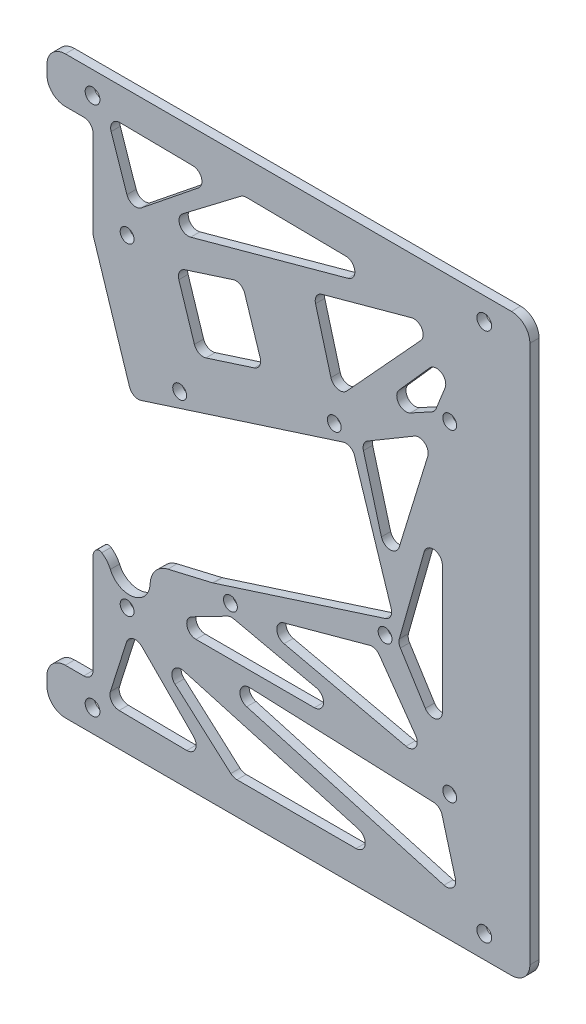
SolidWorks part; units mm, degrees
material "Thornel Mat VMA"
ref_plane "前视基准面" through (0, 0, 0) normal (0, 0, 1) x (1, 0, 0)
ref_plane "上视基准面" through (0, 0, 0) normal (0, 1, 0) x (1, 0, 0)
ref_plane "右视基准面" through (0, 0, 0) normal (1, 0, 0) x (0, 0, -1)
other "Configuration Table"
sketch "草图1" plane through (0, 0, 0) normal (0, 0, 1) x (1, 0, 0)
  line L0 (36.2284, -50.2922) -> (33.3461, -39.7541)
  line L1 (-9.0528, -40.6195) -> (33.7542, -52.7441)
  line L2 (31.4963, -38.2834) -> (-8.4284, -36.6968)
  line L3 (-11.1692, -55.3977) -> (14.6762, -55.3977)
  line L4 (-24.6069, -44.1429) -> (-12.4969, -54.8934)
  line L5 (-44.4, -52.5) -> (-48.4, -52.5)
  line L6 (-52.4, -56.5) -> (-52.4, -58.4)
  line L7 (-48.4, -62.4) -> (48.4, -62.4)
  line L8 (52.4, -58.4) -> (52.4, 58.4)
  line L9 (48.4, 62.4) -> (-48.4, 62.4)
  line L10 (-52.4, 58.4) -> (-52.4, 56.5)
  line L11 (-48.4, 52.5) -> (-44.4, 52.5)
  line L12 (-42.4, 50.5) -> (-42.4, 31.7432)
  line L13 (-42.3041, 31.1312) -> (-34.4768, 6.7761)
  line L14 (-31.9607, 5.484) -> (11.8332, 19.5586)
  line L15 (14.3492, 18.2665) -> (22.3044, -6.4866)
  line L16 (21.0123, -9.0026) -> (-16.2786, -20.9873)
  line L17 (-16.4338, -21.0304) -> (-26.148, -23.3091)
  line L18 (-42.4, -29.0021) -> (-42.4, -50.5)
  line L19 (15.2213, -51.4734) -> (-22.7341, -40.723)
  line L20 (-36.7426, -55.1652) -> (-22.0497, -55.3397)
  line L21 (-35.1169, -41.4884) -> (-38.6254, -52.5612)
  line L22 (-20.6078, -51.9296) -> (-31.7922, -40.6823)
  line L23 (-13.2254, -25.687) -> (-20.9749, -29.6837)
  line L24 (6.0749, -29.509) -> (-11.874, -25.5124)
  line L25 (-20.0582, -33.4612) -> (5.6402, -33.4612)
  line L26 (17.5885, -15.7478) -> (-1.0431, -20.8439)
  line L27 (27.5931, -27.6501) -> (19.7509, -16.5246)
  line L28 (-0.9596, -24.7231) -> (25.5142, -30.7524)
  line L29 (29.4778, 7.7959) -> (24.0664, -11.3096)
  line L30 (33.4021, -20.4793) -> (33.4021, 7.2508)
  line L31 (24.2966, -12.9176) -> (29.708, -21.5423)
  line L32 (24.0261, 5.8622) -> (30.2485, 26.1121)
  line L33 (16.2845, 20.1832) -> (20.1852, 5.922)
  line L34 (27.3184, 28.4209) -> (17.1953, 22.4322)
  line L35 (26.4669, 32.3468) -> (31.1334, 34.8891)
  line L36 (30.6522, 42.9081) -> (24.0145, 35.4309)
  line L37 (32.0339, 35.9035) -> (34.0052, 40.8384)
  line L38 (12.6394, 29.5414) -> (28.7193, 47.0846)
  line L39 (5.8908, 42.5952) -> (9.2359, 30.3651)
  line L40 (26.7173, 50.3651) -> (7.2922, 45.052)
  line L41 (-6.1191, 26.3935) -> (-9.4848, 36.866)
  line L42 (-17.8837, 20.5118) -> (-7.4112, 23.8775)
  line L43 (-23.7654, 32.2764) -> (-20.3997, 21.804)
  line L44 (-12.0008, 38.1581) -> (-22.4732, 34.7925)
  line L45 (-21.2086, 41.5447) -> (12.9544, 50.8889)
  line L46 (-10.3358, 54.6653) -> (-22.9476, 45.0653)
  line L47 (12.4505, 54.8179) -> (-9.1007, 55.0738)
  line L48 (-38.4664, 52.7587) -> (-35.0368, 42.6237)
  line L49 (-20.7385, 55.2119) -> (-36.5482, 55.3996)
  line L50 (-31.8897, 41.7057) -> (-19.5095, 51.653)
  circle A0 centre (-42.5, 57.5) radius 1.6
  circle A1 centre (-23.5962, 11.3233) radius 1.5
  circle A2 centre (-35, 35) radius 1.5
  circle A3 centre (35, 35) radius 1.5
  circle A4 centre (42.5, 57.5) radius 1.6
  circle A5 centre (-42.5, -57.5) radius 1.6
  circle A6 centre (42.5, -57.5) radius 1.6
  circle A7 centre (35, -35) radius 1.5
  arc A8 (-48.4, -52.5) -> (-52.4, -56.5) centre (-48.4, -56.5) ccw
  arc A9 (-52.4, -58.4) -> (-48.4, -62.4) centre (-48.4, -58.4) ccw
  arc A10 (48.4, -62.4) -> (52.4, -58.4) centre (48.4, -58.4) ccw
  arc A11 (52.4, 58.4) -> (48.4, 62.4) centre (48.4, 58.4) ccw
  arc A12 (-48.4, 62.4) -> (-52.4, 58.4) centre (-48.4, 58.4) ccw
  arc A13 (-52.4, 56.5) -> (-48.4, 52.5) centre (-48.4, 56.5) ccw
  arc A14 (-42.4, 50.5) -> (-44.4, 52.5) centre (-44.4, 50.5) ccw
  arc A15 (-42.4, 31.7432) -> (-42.3041, 31.1312) centre (-40.4, 31.7432) ccw
  arc A16 (-34.4768, 6.7761) -> (-31.9607, 5.484) centre (-32.5727, 7.3881) ccw
  arc A17 (14.3492, 18.2665) -> (11.8332, 19.5586) centre (12.4451, 17.6545) ccw
  arc A18 (21.0123, -9.0026) -> (22.3044, -6.4866) centre (20.4003, -7.0985) ccw
  arc A19 (-16.4338, -21.0304) -> (-16.2786, -20.9873) centre (-16.8906, -19.0832) ccw
  arc A20 (-26.148, -23.3091) -> (-30.0029, -27.9976) centre (-25.0061, -28.177) ccw
  arc A21 (-38.6362, -29.6087) -> (-30.0029, -27.9976) centre (-34.5, -27.8362) ccw
  arc A22 (-38.6362, -29.6087) -> (-40.4907, -27.3966) centre (-43.232, -31.5781) ccw
  arc A23 (-40.4907, -27.3966) -> (-41.678, -27.4637) centre (-41.039, -28.2329) ccw
  arc A24 (-41.678, -27.4637) -> (-42.4, -29.0021) centre (-40.4, -29.0021) ccw
  arc A25 (-44.4, -52.5) -> (-42.4, -50.5) centre (-44.4, -50.5) ccw
  circle A26 centre (-35, -35) radius 1.5
  arc A27 (33.7542, -52.7441) -> (36.2284, -50.2922) centre (34.2993, -50.8198) ccw
  arc A28 (-8.4284, -36.6968) -> (-9.0528, -40.6195) centre (-8.5078, -38.6952) ccw
  arc A29 (33.3461, -39.7541) -> (31.4963, -38.2834) centre (31.4169, -40.2818) ccw
  arc A30 (-12.4969, -54.8934) -> (-11.1692, -55.3977) centre (-11.1692, -53.3977) ccw
  arc A31 (-22.7341, -40.723) -> (-24.6069, -44.1429) centre (-23.2792, -42.6473) ccw
  arc A32 (14.6762, -55.3977) -> (15.2213, -51.4734) centre (14.6762, -53.3977) ccw
  arc A33 (-38.6254, -52.5612) -> (-36.7426, -55.1652) centre (-36.7188, -53.1653) ccw
  arc A34 (-31.7922, -40.6823) -> (-35.1169, -41.4884) centre (-33.2104, -42.0925) ccw
  arc A35 (-22.0497, -55.3397) -> (-20.6078, -51.9296) centre (-22.026, -53.3398) ccw
  circle A36 centre (-12.5813, -22.9502) radius 1.5
  arc A37 (-11.874, -25.5124) -> (-13.2254, -25.687) centre (-12.3087, -27.4646) ccw
  arc A38 (5.6402, -33.4612) -> (6.0749, -29.509) centre (5.6402, -31.4612) ccw
  arc A39 (-20.9749, -29.6837) -> (-20.0582, -33.4612) centre (-20.0582, -31.4612) ccw
  circle A40 centre (20.9781, -12.1647) radius 1.5
  circle A41 centre (9.9632, 22.1088) radius 1.5
  arc A42 (19.7509, -16.5246) -> (17.5885, -15.7478) centre (18.1162, -17.6769) ccw
  arc A43 (25.5142, -30.7524) -> (27.5931, -27.6501) centre (25.9583, -28.8024) ccw
  arc A44 (-1.0431, -20.8439) -> (-0.9596, -24.7231) centre (-0.5155, -22.773) ccw
  arc A45 (33.4021, 7.2508) -> (29.4778, 7.7959) centre (31.4021, 7.2508) ccw
  arc A46 (29.708, -21.5423) -> (33.4021, -20.4793) centre (31.4021, -20.4793) ccw
  arc A47 (24.0664, -11.3096) -> (24.2966, -12.9176) centre (25.9907, -11.8546) ccw
  arc A48 (20.1852, 5.922) -> (24.0261, 5.8622) centre (22.1143, 6.4496) ccw
  arc A49 (17.1953, 22.4322) -> (16.2845, 20.1832) centre (18.2136, 20.7109) ccw
  arc A50 (30.2485, 26.1121) -> (27.3184, 28.4209) centre (28.3367, 26.6996) ccw
  arc A51 (24.0145, 35.4309) -> (26.4669, 32.3468) centre (25.5101, 34.1031) ccw
  arc A52 (34.0052, 40.8384) -> (30.6522, 42.9081) centre (32.1479, 41.5803) ccw
  arc A53 (31.1334, 34.8891) -> (32.0339, 35.9035) centre (30.1766, 36.6454) ccw
  arc A54 (9.2359, 30.3651) -> (12.6394, 29.5414) centre (11.165, 30.8927) ccw
  arc A55 (7.2922, 45.052) -> (5.8908, 42.5952) centre (7.8199, 43.1229) ccw
  arc A56 (28.7193, 47.0846) -> (26.7173, 50.3651) centre (27.245, 48.436) ccw
  arc A57 (-9.4848, 36.866) -> (-12.0008, 38.1581) centre (-11.3889, 36.2541) ccw
  arc A58 (-7.4112, 23.8775) -> (-6.1191, 26.3935) centre (-8.0232, 25.7816) ccw
  arc A59 (-20.3997, 21.804) -> (-17.8837, 20.5118) centre (-18.4956, 22.4159) ccw
  arc A60 (-22.4732, 34.7925) -> (-23.7654, 32.2764) centre (-21.8613, 32.8884) ccw
  arc A61 (-22.9476, 45.0653) -> (-21.2086, 41.5447) centre (-21.7363, 43.4739) ccw
  arc A62 (-9.1007, 55.0738) -> (-10.3358, 54.6653) centre (-9.1244, 53.0739) ccw
  arc A63 (12.9544, 50.8889) -> (12.4505, 54.8179) centre (12.4267, 52.818) ccw
  arc A64 (-36.5482, 55.3996) -> (-38.4664, 52.7587) centre (-36.5719, 53.3998) ccw
  arc A65 (-19.5095, 51.653) -> (-20.7385, 55.2119) centre (-20.7622, 53.2121) ccw
  arc A66 (-35.0368, 42.6237) -> (-31.8897, 41.7057) centre (-33.1424, 43.2647) ccw
extrude "凸台-拉伸1" add sketch "草图1" along normal blind 2
